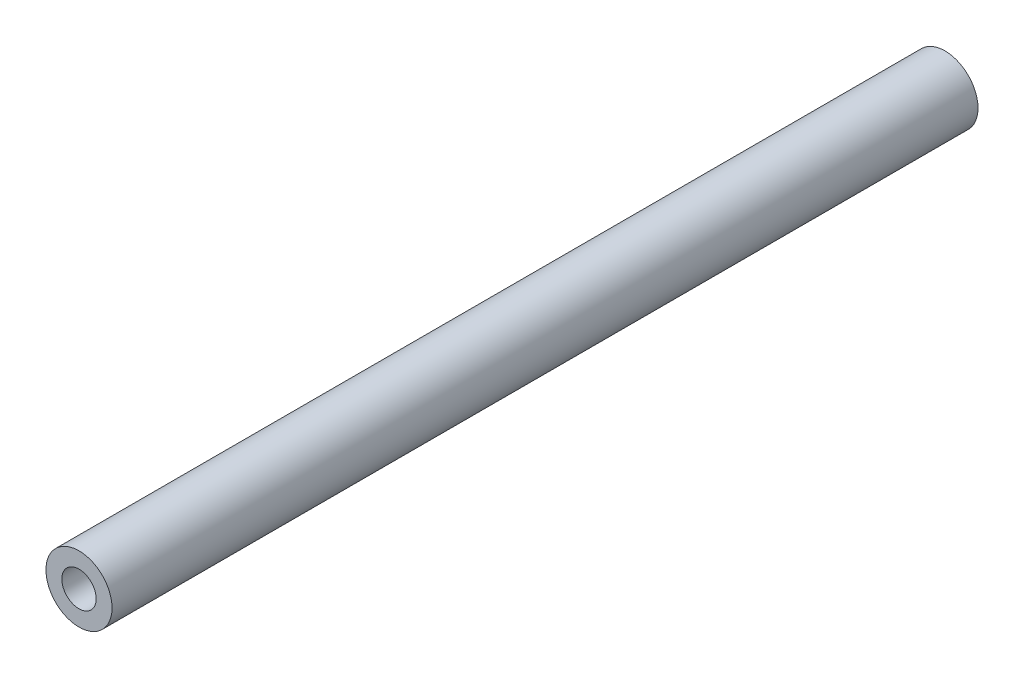
SolidWorks part; units mm, degrees
ref_plane "Front Plane" through (0, 0, 0) normal (0, 0, 1) x (1, 0, 0)
ref_plane "Top Plane" through (0, 0, 0) normal (0, 1, 0) x (1, 0, 0)
ref_plane "Right Plane" through (0, 0, 0) normal (1, 0, 0) x (0, 0, -1)
sketch "Sketch1" plane through (0, 0, 0) normal (0, 0, 1) x (1, 0, 0)
  circle A0 centre (0, 0) radius 2.5
extrude "Boss-Extrude1" add sketch "Sketch1" along normal blind 65.5
sketch "Sketch2" plane through (0, 0, 65.5) normal (0, 0, 1) x (1, 0, 0)
  point P0 (0, 0)
hole_wizard "M3x0.5 Tapped Hole1" positions "Sketch2" profile "Sketch3" tap size "M3x0.5" standard "JIS"
sketch "Sketch3" plane through (0, 0, 65.5) normal (1, 0, 0) x (0, -1, 0)
  line L0 (0, 0) -> (0, 8.7811)
  line L1 (0, 8.7811) -> (1.3, 8)
  line L2 (1.3, 8) -> (1.3, 0)
  line L5 (1.3, 0) -> (0, 0)
  line L10 (0, 8.7811) -> (-1.3, 8) construction
  line L11 (0, -6.35) -> (0, 107.95) construction
  dimension "Tap Drill Dia." = 2.6
  dimension "Tap Drill Depth" = 8
  dimension "Drill Angle" = 118
cosmetic thread "Hole Thread1"
sketch "Sketch4" plane through (0, 0, 0) normal (0, 0, -1) x (-1, 0, 0)
  point P0 (0, 0)
hole_wizard "M3x0.5 Tapped Hole2" positions "Sketch4" profile "Sketch5" tap size "M3x0.5" standard "JIS"
sketch "Sketch5" plane through (0, 0, 0) normal (1, 0, 0) x (0, 1, 0)
  line L0 (0, 0) -> (0, 8.7811)
  line L1 (0, 8.7811) -> (1.3, 8)
  line L2 (1.3, 8) -> (1.3, 0)
  line L5 (1.3, 0) -> (0, 0)
  line L10 (0, 8.7811) -> (-1.3, 8) construction
  line L11 (0, -6.35) -> (0, 107.95) construction
  dimension "Tap Drill Dia." = 2.6
  dimension "Tap Drill Depth" = 8
  dimension "Drill Angle" = 118
cosmetic thread "Hole Thread2"
